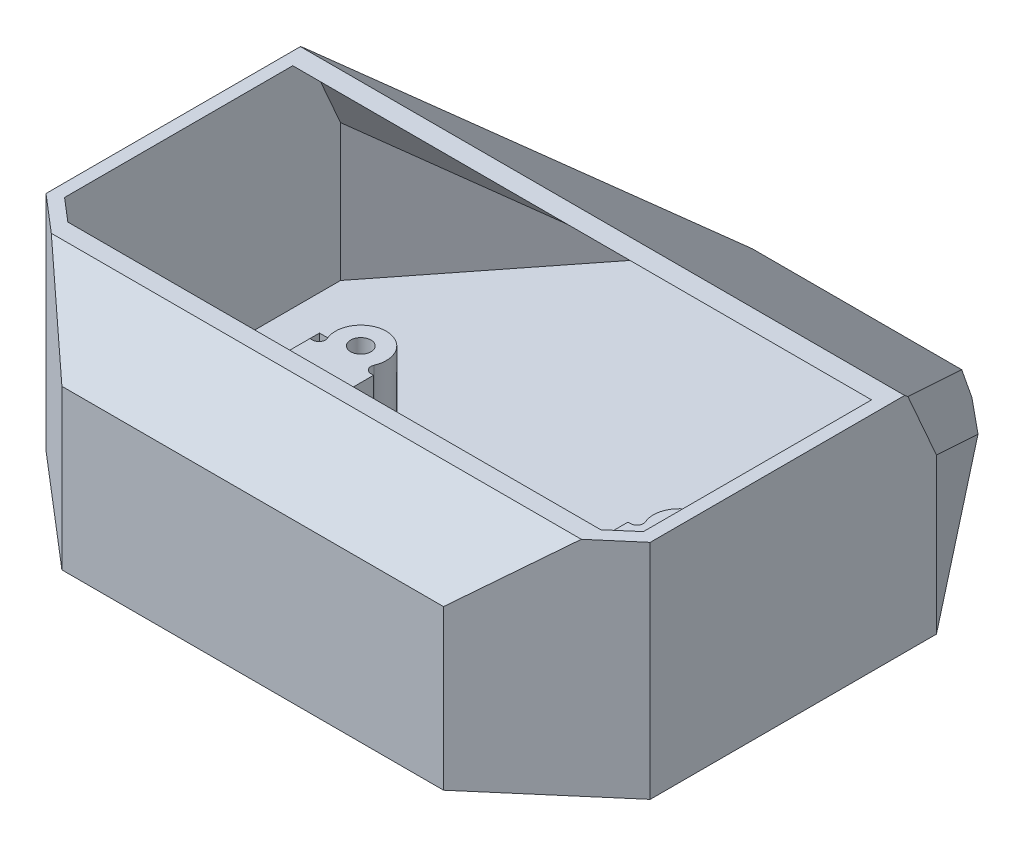
SolidWorks part; units mm, degrees
ref_plane "Ebene vorne" through (0, 0, 0) normal (0, 0, 1) x (1, 0, 0)
ref_plane "Ebene oben" through (0, 0, 0) normal (0, 1, 0) x (1, 0, 0)
ref_plane "Ebene rechts" through (0, 0, 0) normal (1, 0, 0) x (0, 0, -1)
sketch "Skizze6" plane through (0, 0, 0) normal (0, 1, 0) x (1, 0, 0)
  line L0 (-47.5, 0) -> (47.5, 0) construction
  line L1 (0, 0) -> (0, 60) construction
  line L2 (0, 0) -> (0, -35) construction
  line L3 (30, -35) -> (-30, -35)
  line L4 (-30, -35) -> (-47.5, -20)
  line L5 (-47.5, -20) -> (-47.5, 25)
  line L6 (-47.5, 25) -> (-20, 60)
  line L7 (-20, 60) -> (20, 60)
  line L8 (30, -35) -> (47.5, -20)
  line L9 (47.5, -20) -> (47.5, 25)
  line L10 (47.5, 25) -> (20, 60)
  point P14 (-47.5, 0)
  dimension "D1" = 95
  dimension "D2" = 95
  dimension "D3" = 60
  dimension "D4" = 40
  dimension "D5" = 45
  dimension "D6" = 60
  dimension "D7" = 20
extrude "Aufsatz-Linear austragen1" add sketch "Skizze6" along normal blind 35
ref_plane "Ebene3" through (0, 0, 0) normal (1, 0, 0) x (0, 0, -1)
sketch "Skizze8" plane through (0, 0, 0) normal (1, 0, 0) x (0, 0, -1)
  line L0 (20, 35) -> (60, 3)
  line L1 (-20, 35) -> (25, 35) construction
  line L2 (60, 35) -> (60, 0) construction
  line L3 (60, 3) -> (60, 35)
  line L4 (25, 35) -> (60, 35) construction
  line L5 (60, 35) -> (20, 35)
  line L6 (25, 0) -> (60, 0) construction
  dimension "D1" = 55
  dimension "D2" = 3
extrude "Schnitt-Linear austragen1" cut sketch "Skizze8" against normal through all and the other way through all
chamfer "Fase6" distance 3 angle 45 2 edges at (33.75, 17, -42.5) (-33.75, 17, -42.5)
chamfer "Fase7" distance 10 angle 45 1 edges at (0, 35, 35)
shell "Wandung3" thickness 2
sketch "Skizze9" plane through (0, 0, 0) normal (0, -1, 0) x (1, 0, 0)
  line L0 (35, 2) -> (-35, 2) construction
  line L1 (0, -19.25) -> (0, 19.25) construction
  line L2 (30, -15.5) -> (40, 19.5) construction
  line L3 (-30, 19.5) -> (-40, 19.5)
  line L4 (-30, 19.5) -> (-30, -15.5)
  line L5 (-30, -15.5) -> (-40, -15.5)
  line L6 (-40, 19.5) -> (-40, -15.5)
  line L7 (-30, 19.5) -> (-40, -15.5) construction
  line L8 (-30, -15.5) -> (-40, 19.5) construction
  line L9 (30, 19.5) -> (40, -15.5) construction
  line L10 (40, 19.5) -> (40, -15.5)
  line L11 (30, -15.5) -> (40, -15.5)
  line L12 (30, 19.5) -> (30, -15.5)
  line L13 (30, 19.5) -> (40, 19.5)
  point P13 (0, 2)
  dimension "D1" = 35
  dimension "D2" = 10
  dimension "D3" = 70
  dimension "D4" = 2
extrude "Schnitt-Linear austragen2" cut sketch "Skizze9" against normal up to next
sketch "Skizze10" plane through (0, 2, 0) normal (0, 1, 0) x (1, 0, 0)
  line L0 (-30, -2) -> (30, -2) construction
  line L1 (-30, 15.5) -> (-30, -19.5) construction
  line L2 (30, -19.5) -> (30, 15.5) construction
  line L4 (-30, 4) -> (-27.6458, 4)
  line L5 (-30, 4) -> (-30, -8)
  line L6 (-30, -8) -> (-27.6458, -8)
  line L7 (-20, 4) -> (-20, -8)
  line L8 (-30, 4) -> (-20, -8) construction
  line L9 (-30, -8) -> (-20, 4) construction
  line L10 (0, -19.25) -> (0, 19.25) construction
  line L11 (25, -2) -> (25, 7) construction
  line L16 (-25, 5.4) -> (-25, 7) construction
  line L17 (-22.3542, 4) -> (-20, 4)
  line L18 (-22.3542, -8) -> (-20, -8)
  line L19 (-25, -2) -> (-25, 7) construction
  line L20 (25, 5.4) -> (25, 7) construction
  line L21 (30, -8) -> (20, 4) construction
  line L22 (30, 4) -> (20, -8) construction
  line L23 (22.3542, -8) -> (20, -8)
  line L24 (22.3542, 4) -> (20, 4)
  line L25 (20, 4) -> (20, -8)
  line L26 (30, -8) -> (27.6458, -8)
  line L27 (30, 4) -> (30, -8)
  line L28 (30, 4) -> (27.6458, 4)
  circle A0 centre (-25, 7) radius 1.6
  circle A1 centre (-25, -11) radius 1.6
  arc A2 (-22.3542, 4) -> (-27.6458, 4) centre (-25, 7) ccw
  arc A3 (-22.3542, -8) -> (-27.6458, -8) centre (-25, -11) cw
  arc A4 (22.3542, -8) -> (27.6458, -8) centre (25, -11) ccw
  arc A5 (22.3542, 4) -> (27.6458, 4) centre (25, 7) cw
  circle A6 centre (25, -11) radius 1.6
  circle A7 centre (25, 7) radius 1.6
  point P6 (-25, -2)
  dimension "D3" = 3.2
  dimension "D4" = 18
  dimension "D5" = 8
  dimension "D1" = 12
  dimension "D2" = 10
extrude "Aufsatz-Linear austragen3" add sketch "Skizze10" along normal blind 10
fillet "Verrundung4" radius 1 8 edges at (27.6458, 7, 8) (27.6458, 7, -4) (22.3542, 7, -4) (22.3542, 7, 8) (-27.6458, 7, -4) (-22.3542, 7, -4) (-27.6458, 7, 8) (-22.3542, 7, 8)
